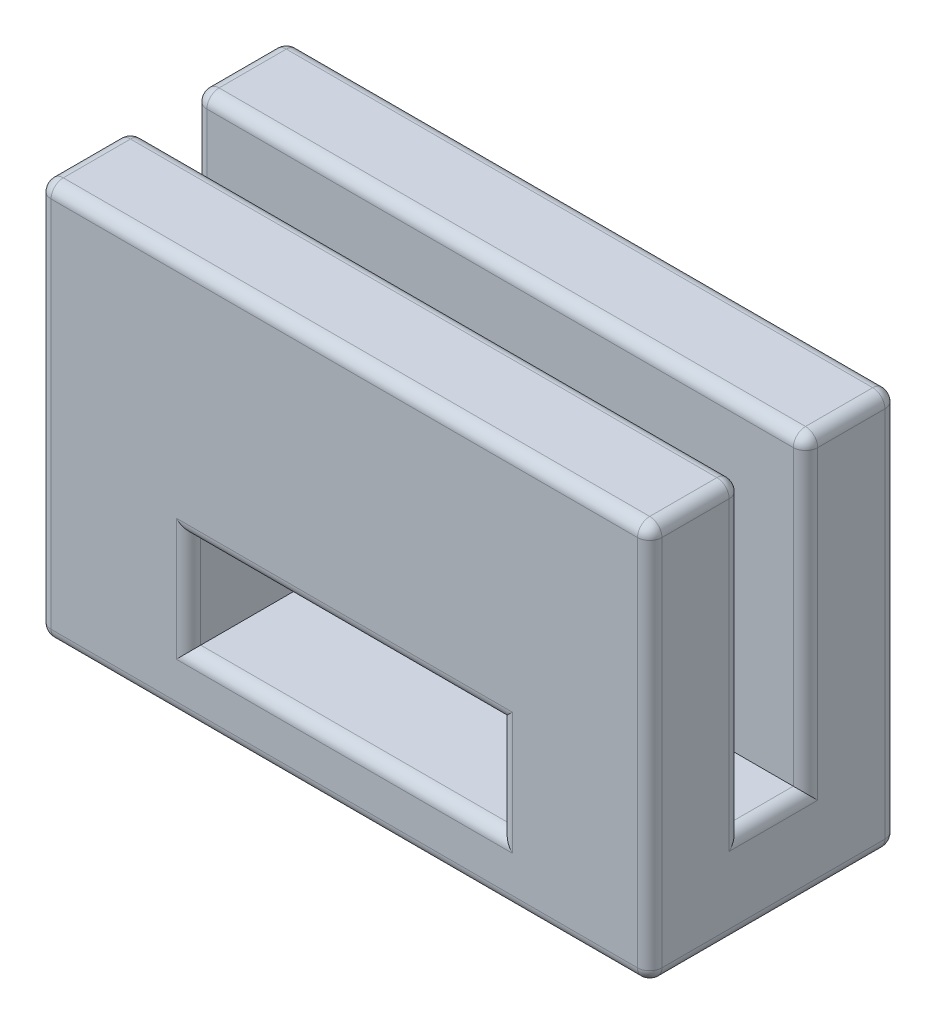
SolidWorks part; units mm, degrees
ref_plane "Front Plane" through (0, 0, 0) normal (0, 0, 1) x (1, 0, 0)
ref_plane "Top Plane" through (0, 0, 0) normal (0, 1, 0) x (1, 0, 0)
ref_plane "Right Plane" through (0, 0, 0) normal (1, 0, 0) x (0, 0, -1)
sketch "Sketch1" plane through (0, 0, 0) normal (0, 1, 0) x (1, 0, 0)
  line L1 (0, 0) -> (20, 0)
  line L2 (0, 0) -> (0, -8.1)
  line L3 (0, -8.1) -> (20, -8.1)
  line L4 (20, 0) -> (20, -8.1)
  dimension "D1" = 8.1
  dimension "D2" = 20
extrude "Boss-Extrude1" add sketch "Sketch1" along normal blind 3
sketch "Sketch2" plane through (0, 3, 0) normal (0, 1, 0) x (1, 0, 0)
  line L0 (20, -8.1) -> (20, 0) construction
  line L1 (0, 0) -> (20, 0)
  line L2 (0, 0) -> (0, -3)
  line L3 (0, -3) -> (20, -3)
  line L4 (20, 0) -> (20, -3)
  line L6 (0, -8.1) -> (20, -8.1)
  line L7 (0, -8.1) -> (0, -5.1)
  line L8 (0, -5.1) -> (20, -5.1)
  line L9 (20, -8.1) -> (20, -5.1)
  dimension "D1" = 3
  dimension "D2" = 3
extrude "Boss-Extrude2" add sketch "Sketch2" along normal blind 10
sketch "Sketch3" plane through (0, 0, 0) normal (0, 0, -1) x (-1, 0, 0)
  line L0 (-20, 0) -> (0, 0) construction
  line L1 (-15.1, 5.2) -> (-4.9, 5.2)
  line L2 (-15.1, 5.2) -> (-15.1, 2)
  line L3 (-15.1, 2) -> (-4.9, 2)
  line L4 (-4.9, 5.2) -> (-4.9, 2)
  point P4 (-10, 2)
  point P7 (-10, 0)
  dimension "D1" = 3.2
  dimension "D2" = 10.2
  dimension "D3" = 0
  dimension "D4" = 2
extrude "Cut-Extrude1" cut sketch "Sketch3" against normal through all
fillet "Fillet1" radius 0.4 30 edges at (10, 13, 5.1) (10, 13, 3) (20, 13, 6.6) (20, 8, 5.1) (20, 3, 4.05) (20, 8, 3) (20, 13, 1.5) (0, 13, 1.5) (0, 8, 3) (0, 3, 4.05) (0, 8, 5.1) (0, 13, 6.6) (20, 6.5, 0) (10, 13, 0) (0, 6.5, 0) (4.9, 3.6, 0) (10, 5.2, 0) (15.1, 3.6, 0) (10, 2, 0) (20, 0, 4.05) (10, 0, 0) (0, 0, 4.05) (0, 6.5, 8.1) (10, 13, 8.1) (20, 6.5, 8.1) (10, 0, 8.1) (4.9, 3.6, 8.1) (10, 2, 8.1) (15.1, 3.6, 8.1) (10, 5.2, 8.1)
